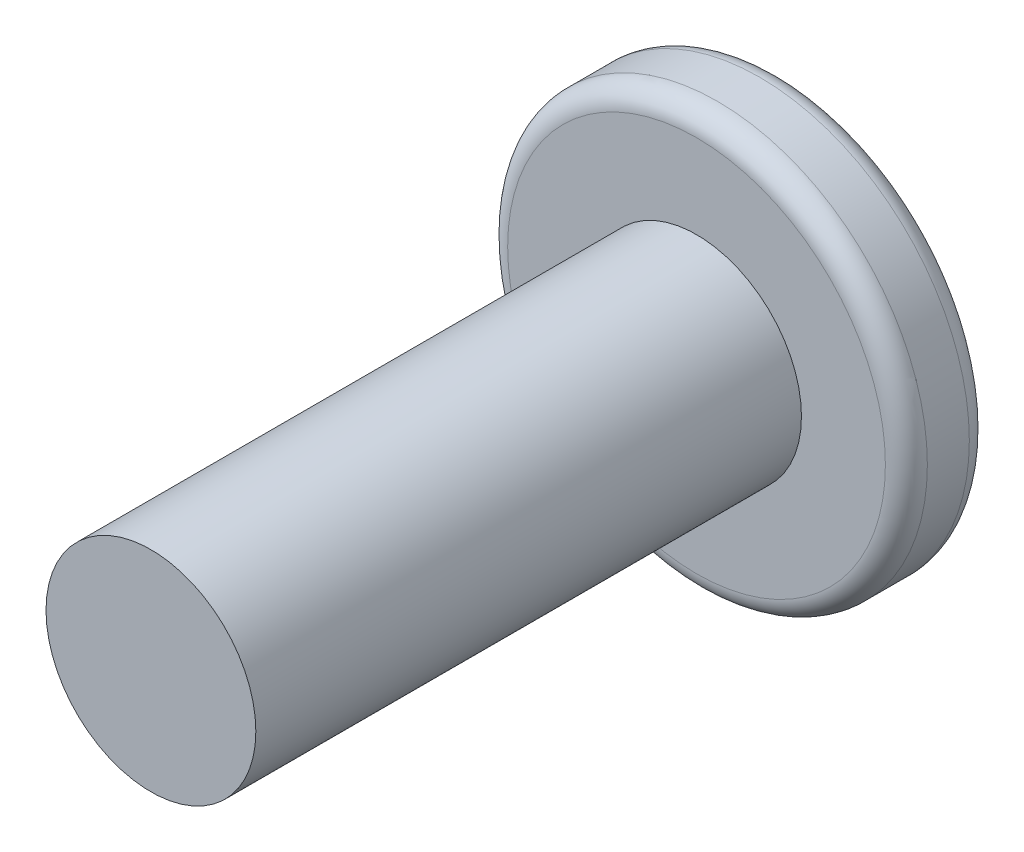
SolidWorks part; units mm, degrees
ref_plane "前视基准面" through (0, 0, 0) normal (0, 0, 1) x (1, 0, 0)
ref_plane "上视基准面" through (0, 0, 0) normal (0, 1, 0) x (1, 0, 0)
ref_plane "右视基准面" through (0, 0, 0) normal (1, 0, 0) x (0, 0, -1)
sketch "草图1" plane through (0, 0, 0) normal (0, 1, 0) x (1, 0, 0)
  line L2 (0, 0) -> (0, -5.2)
  line L3 (0, -5.2) -> (1, -5.2)
  line L4 (1, 0) -> (1, -5.2)
  line L5 (1, 0) -> (1.8, 0)
  line L6 (0, 0) -> (0, 0.8)
  line L7 (0, 0.8) -> (1.8, 0.8)
  line L8 (2, 0.2) -> (2, 0.6)
  arc A0 (1.8, 0) -> (2, 0.2) centre (1.8, 0.2) ccw
  arc A1 (1.8, 0.8) -> (2, 0.6) centre (1.8, 0.6) cw
  point P10 (2, 0)
  point P13 (2, 0.8)
  dimension "D5" = 0.2
  dimension "D1" = 6
  dimension "D2" = 0.8
  dimension "D3" = 2
  dimension "D4" = 1
revolve "旋转1" add sketch "草图1" angle 360 about L2
sketch "草图2" plane through (0, 0, -0.8) normal (0, 0, -1) x (-1, 0, 0)
  line L11 (0, 1.1) -> (-0.2, 1.1)
  line L12 (-0.2, 0.3) -> (-0.2, 1.1)
  line L15 (0, 1.1) -> (0.2, 1.1)
  line L16 (0.2, 0.3) -> (0.2, 1.1)
  line L19 (0.3, -0.2) -> (1.1, -0.2)
  line L20 (1.1, 0) -> (1.1, -0.2)
  line L23 (0.3, 0.2) -> (1.1, 0.2)
  line L24 (1.1, 0) -> (1.1, 0.2)
  line L27 (0, -1.1) -> (-0.2, -1.1)
  line L28 (-0.2, -0.3) -> (-0.2, -1.1)
  line L31 (0, -1.1) -> (0.2, -1.1)
  line L32 (0.2, -0.3) -> (0.2, -1.1)
  line L35 (-0.3, 0.2) -> (-1.1, 0.2)
  line L36 (-1.1, 0) -> (-1.1, 0.2)
  line L39 (-0.3, -0.2) -> (-1.1, -0.2)
  line L40 (-1.1, 0) -> (-1.1, -0.2)
  arc A0 (-0.2, 0.3) -> (-0.3, 0.2) centre (-0.3, 0.3) cw
  arc A1 (-0.2, -0.3) -> (-0.3, -0.2) centre (-0.3, -0.3) ccw
  arc A2 (0.2, -0.3) -> (0.3, -0.2) centre (0.3, -0.3) cw
  arc A3 (0.3, 0.2) -> (0.2, 0.3) centre (0.3, 0.3) cw
  dimension "D1" = 0.1
extrude "切除-拉伸1" [suppressed] cut sketch "草图2" against normal blind 0.5
sketch "草图3" plane through (0, 0, -0.8) normal (0, 0, -1) x (-1, 0, 0)
  line L1 (0.866, 0) -> (0.433, 0.75)
  line L2 (0.433, 0.75) -> (-0.433, 0.75)
  line L3 (-0.433, 0.75) -> (-0.866, 0)
  line L4 (-0.866, 0) -> (-0.433, -0.75)
  line L5 (-0.433, -0.75) -> (0.433, -0.75)
  line L6 (0.433, -0.75) -> (0.866, 0)
  circle A0 centre (0, 0) radius 0.75 construction
  dimension "D1" = 1.5
extrude "切除-拉伸2" cut sketch "草图3" against normal blind 1.5
